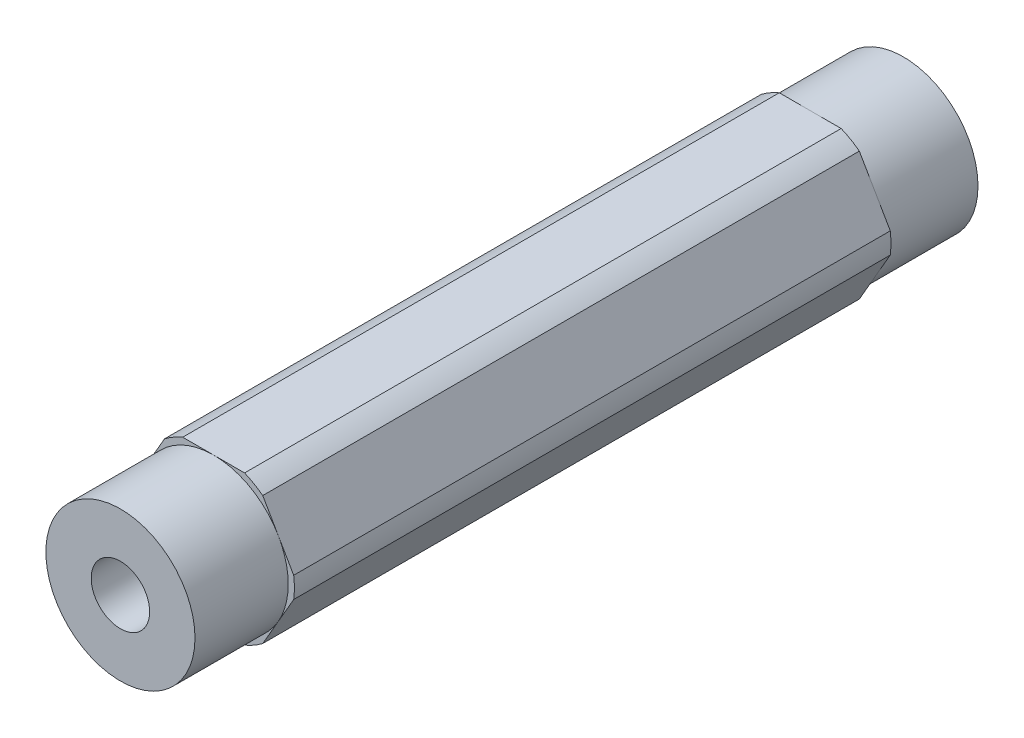
SolidWorks part; units mm, degrees
material "7075-T6 (SN)"
ref_plane "Front Plane" through (0, 0, 0) normal (0, 0, 1) x (1, 0, 0)
ref_plane "Top Plane" through (0, 0, 0) normal (0, 1, 0) x (1, 0, 0)
ref_plane "Right Plane" through (0, 0, 0) normal (1, 0, 0) x (0, 0, -1)
sketch "Sketch1" plane through (0, 0, 0) normal (0, 0, 1) x (1, 0, 0)
  line L1 (-3.6662, 6.35) -> (-7.3323, 0)
  line L2 (-7.3323, 0) -> (-3.6662, -6.35)
  line L3 (-3.6662, -6.35) -> (3.6662, -6.35)
  line L4 (3.6662, -6.35) -> (7.3323, 0)
  line L5 (7.3323, 0) -> (3.6662, 6.35)
  line L6 (3.6662, 6.35) -> (-3.6662, 6.35)
  circle A0 centre (0, 0) radius 6.875
  circle A1 centre (0, 0) radius 6.35 construction
  circle A2 centre (0, 0) radius 2.4892
  point P12 (0, 6.35)
  dimension "D1" = 12.7
  dimension "D2" = 13.75
  dimension "D3" = 4.9784
extrude "Boss-Extrude1" add sketch "Sketch1" along normal mid plane 66.675 contours L5 A0 L6 L1 L2 L3 L4
sketch "Sketch2" plane through (0, 0, 33.3375) normal (0, 0, 1) x (1, 0, 0)
  circle A0 centre (0, 0) radius 6.35
  line M2 (6.8168, 0.893) -> (4.1818, 5.457)
  arc M3 (4.1818, 5.457) -> (2.635, 6.35) centre (0, 0) ccw
  line M4 (2.635, 6.35) -> (-2.635, 6.35)
  arc M5 (-2.635, 6.35) -> (-4.1818, 5.457) centre (0, 0) ccw
  line M6 (-4.1818, 5.457) -> (-6.8168, 0.893)
  arc M7 (-6.8168, 0.893) -> (-6.8168, -0.893) centre (0, 0) ccw
  line M8 (-6.8168, -0.893) -> (-4.1818, -5.457)
  arc M9 (-4.1818, -5.457) -> (-2.635, -6.35) centre (0, 0) ccw
  line M10 (-2.635, -6.35) -> (2.635, -6.35)
  arc M11 (2.635, -6.35) -> (4.1818, -5.457) centre (0, 0) ccw
  line M12 (4.1818, -5.457) -> (6.8168, -0.893)
  arc M13 (6.8168, -0.893) -> (6.8168, 0.893) centre (0, 0) ccw
  dimension "D1" = 12.7
extrude "Cut-Extrude2" cut sketch "Sketch2" against normal blind 7.9375 contours A0 M4 M5 M6 | A0 M2 M3 M4 | A0 M12 M13 M2 | A0 M10 M11 M12 | A0 M8 M9 M10 | A0 M6 M7 M8
mirror "Mirror1" about plane through (0, 0, 0) normal (0, 0, 1) of "Cut-Extrude2"
equation "\"D2@Sketch1\"=13.75mm"
